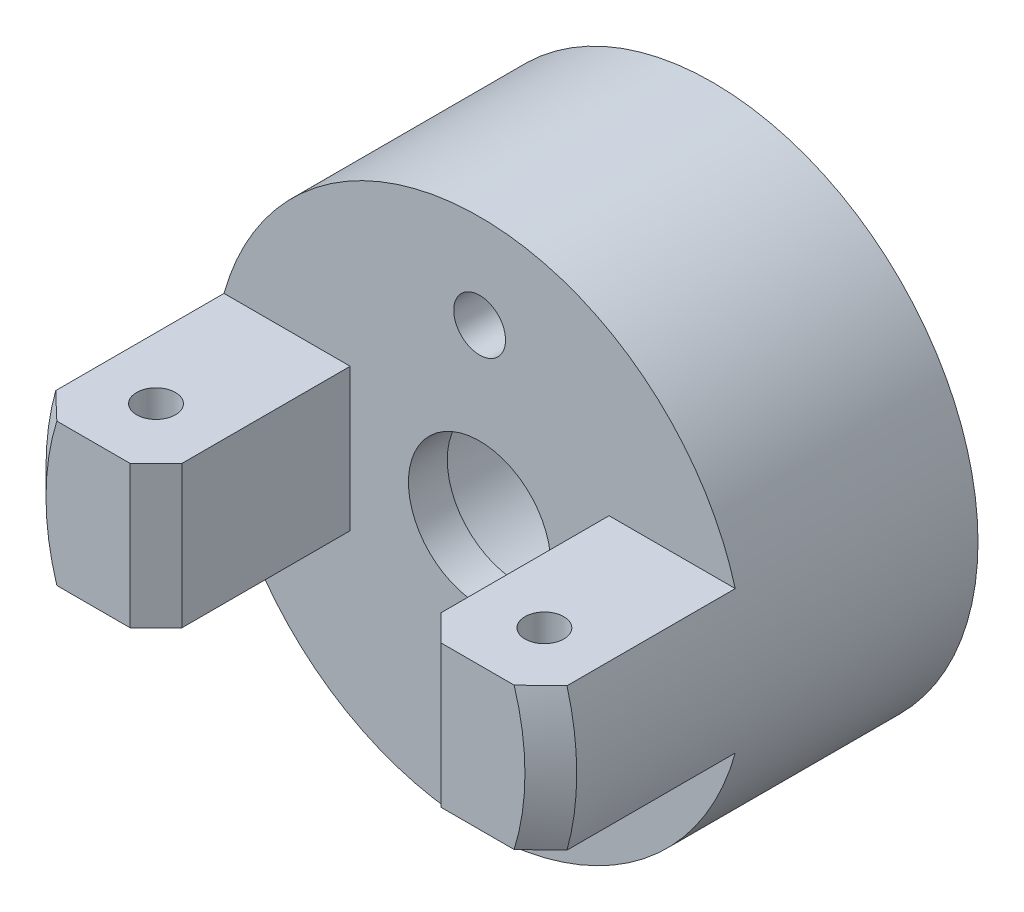
SolidWorks part; units mm, degrees
ref_plane "Спереди" through (0, 0, 0) normal (0, 0, 1) x (1, 0, 0)
ref_plane "Сверху" through (0, 0, 0) normal (0, 1, 0) x (1, 0, 0)
ref_plane "Справа" through (0, 0, 0) normal (1, 0, 0) x (0, 0, -1)
sketch "Эскиз1" plane through (0, 0, 0) normal (0, 0, 1) x (1, 0, 0)
  circle A0 centre (0, 0) radius 20.5
  dimension "D1" = 41
extrude "Вытянуть1" add sketch "Эскиз1" along normal blind 33
sketch "Эскиз2" plane through (0, 0, 33) normal (0, 0, 1) x (1, 0, 0)
  line L0 (10, 5.5) -> (24.4024, 5.5)
  line L1 (-29.0568, 27.1663) -> (24.4024, 27.1663)
  line L2 (-29.0568, 27.1663) -> (-29.0568, 5.5)
  line L3 (-29.0568, 5.5) -> (-10, 5.5)
  line L4 (24.4024, 27.1663) -> (24.4024, 5.5)
  line L5 (-25.1523, -5.5) -> (-10, -5.5)
  line L6 (-25.1523, -5.5) -> (-25.1523, -27.5157)
  line L7 (-25.1523, -27.5157) -> (25.5379, -27.5157)
  line L8 (25.5379, -5.5) -> (25.5379, -27.5157)
  line L9 (10, -5.5) -> (25.5379, -5.5)
  line L10 (-10, 5.5) -> (-10, -5.5)
  line L12 (10, 5.5) -> (10, -5.5)
  dimension "D1" = 11
  dimension "D2" = 5.5
  dimension "D3" = 20
  dimension "D4" = 10
extrude "Вырез-Вытянуть1" cut sketch "Эскиз2" against normal blind 15
sketch "Эскиз3" plane through (0, 0, 18) normal (0, 0, 1) x (1, 0, 0)
  line L0 (0, 0) -> (0, 13.25) construction
  line L1 (0, 13.25) -> (0, -13.25) construction
  circle A0 centre (0, 0) radius 5
  circle A1 centre (0, 13.25) radius 2
  circle A2 centre (0, -13.25) radius 2
  dimension "D1" = 26.5
  dimension "D2" = 13.25
extrude "Вырез-Вытянуть2" cut sketch "Эскиз3" against normal through all
chamfer "Фаска1" distance 2 angle 45 4 edges at (20.5, 0, 33) (-20.5, 0, 33) (-10, 0, 33) (10, 0, 33)
sketch "Эскиз4" plane through (0, -5.5, 0) normal (0, -1, 0) x (1, 0, 0)
  line L0 (-10, 18) -> (-10, 31) construction
  line L1 (-12, 33) -> (-17.6635, 33) construction
  line L2 (-14.5333, 28) -> (-15, 28) construction
  line L3 (-15, 28) -> (20.9695, 28) construction
  circle A0 centre (-15, 28) radius 1.5
  circle A1 centre (15, 28) radius 1.5
  dimension "D1" = 3
  dimension "D2" = 3
  dimension "D3" = 30
  dimension "D4" = 5
  dimension "D5" = 5
extrude "Вырез-Вытянуть3" cut sketch "Эскиз4" against normal blind 15
sketch "Эскиз6" plane through (0, 0, 18) normal (0, 0, 1) x (1, 0, 0)
  circle A0 centre (0, 0) radius 5.5
  dimension "D1" = 11
extrude "Вырез-Вытянуть4" cut sketch "Эскиз6" against normal through all
sketch "Эскиз9" plane through (0, 0, 0) normal (0, 0, -1) x (-1, 0, 0)
  circle A0 centre (0, 0) radius 7.5
extrude "Вырез-Вытянуть7" cut sketch "Эскиз9" against normal blind 15
